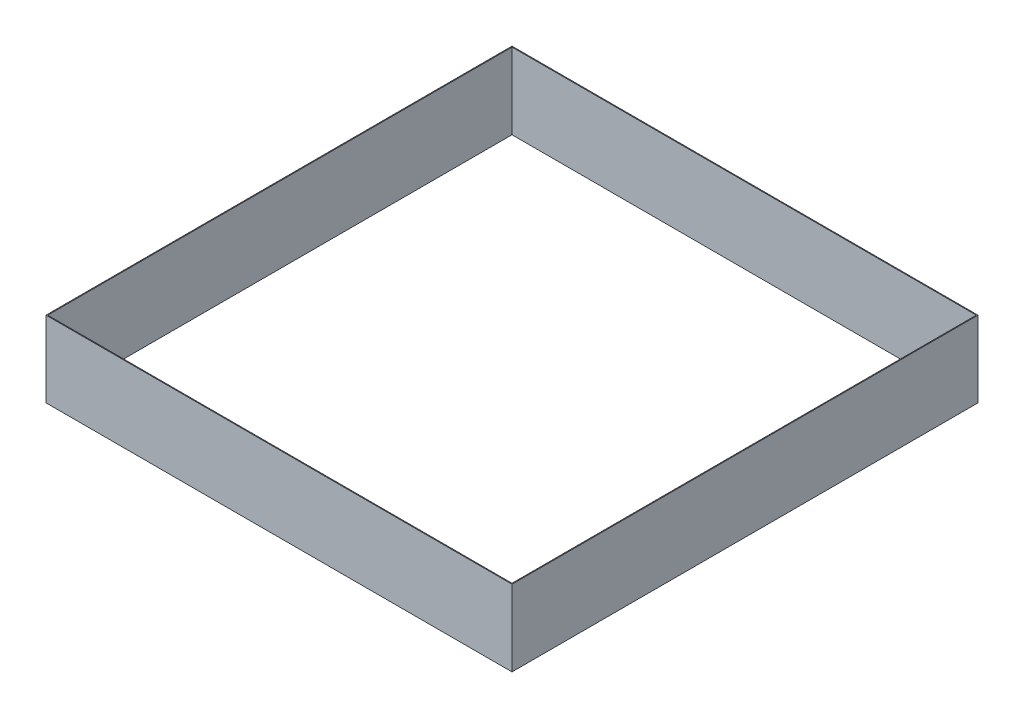
SolidWorks part; units mm, degrees
ref_plane "前视基准面" through (0, 0, 0) normal (0, 0, 1) x (1, 0, 0)
ref_plane "上视基准面" through (0, 0, 0) normal (0, 1, 0) x (1, 0, 0)
ref_plane "右视基准面" through (0, 0, 0) normal (1, 0, 0) x (0, 0, -1)
sketch "草图1" plane through (0, 0, 0) normal (0, 1, 0) x (1, 0, 0)
  line L0 (0, 0) -> (0, -331.2)
  line L1 (0, -331.2) -> (331.2, -331.2)
  line L2 (331.2, -331.2) -> (331.2, 0)
  line L3 (331.2, 0) -> (0, 0)
  line L4 (0.6, -0.6) -> (0.6, -330.6)
  line L5 (0.6, -330.6) -> (330.6, -330.6)
  line L6 (330.6, -330.6) -> (330.6, -0.6)
  line L7 (330.6, -0.6) -> (0.6, -0.6)
  dimension "D1" = 330
  dimension "D2" = 330
  dimension "D3" = 0.6
  dimension "D4" = 0.6
  dimension "D5" = 0.6
  dimension "D6" = 0.6
extrude "凸台-拉伸1" add sketch "草图1" along normal blind 54
